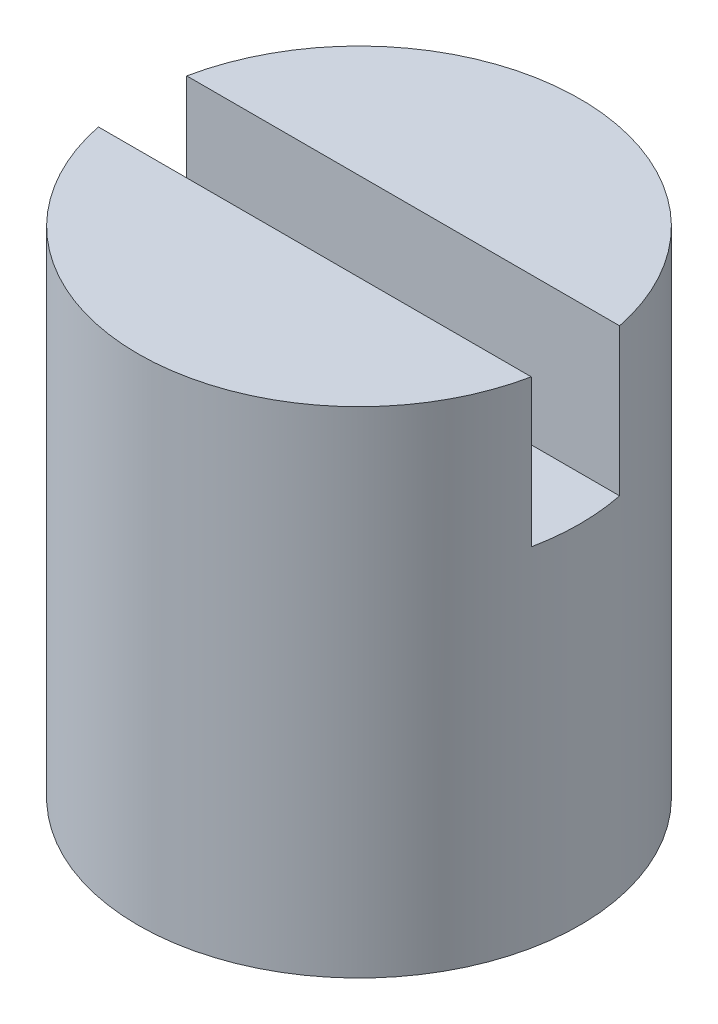
SolidWorks part; units mm, degrees
material "6061-T6 (SS)"
ref_plane "X-Y Datum" through (0, 0, 0) normal (0, 0, 1) x (1, 0, 0)
ref_plane "X-Z Datum" through (0, 0, 0) normal (0, 1, 0) x (1, 0, 0)
ref_plane "Y-Z Datum" through (0, 0, 0) normal (1, 0, 0) x (0, 0, -1)
sketch "Sketch1" plane through (0, 0, 0) normal (0, 1, 0) x (1, 0, 0)
  circle A0 centre (0, 0) radius 4.7625
  dimension "D1" = 9.525
extrude "Boss-Extrude1" add sketch "Sketch1" against normal blind 10.668
sketch "Sketch2" plane through (0, 0, 0) normal (0, 1, 0) x (1, 0, 0)
  line L5 (4.7625, 0.9525) -> (-4.7625, 0.9525)
  line L6 (4.7625, 0.9525) -> (4.7625, -0.9525)
  line L7 (4.7625, -0.9525) -> (-4.7625, -0.9525)
  line L8 (-4.7625, 0.9525) -> (-4.7625, -0.9525)
  line L9 (4.7625, 0.9525) -> (-4.7625, -0.9525) construction
  line L10 (4.7625, -0.9525) -> (-4.7625, 0.9525) construction
  point P0 (0, 0)
  dimension "D1" = 9.525
  dimension "D2" = 1.905
extrude "Cut-Extrude1" cut sketch "Sketch2" against normal blind 3.175
sketch "Sketch3" plane through (0, -10.668, 0) normal (0, -1, 0) x (1, 0, 0)
  circle A0 centre (0, 0) radius 2
  dimension "D1" = 4
extrude "Cut-Extrude2" cut sketch "Sketch3" against normal blind 5
